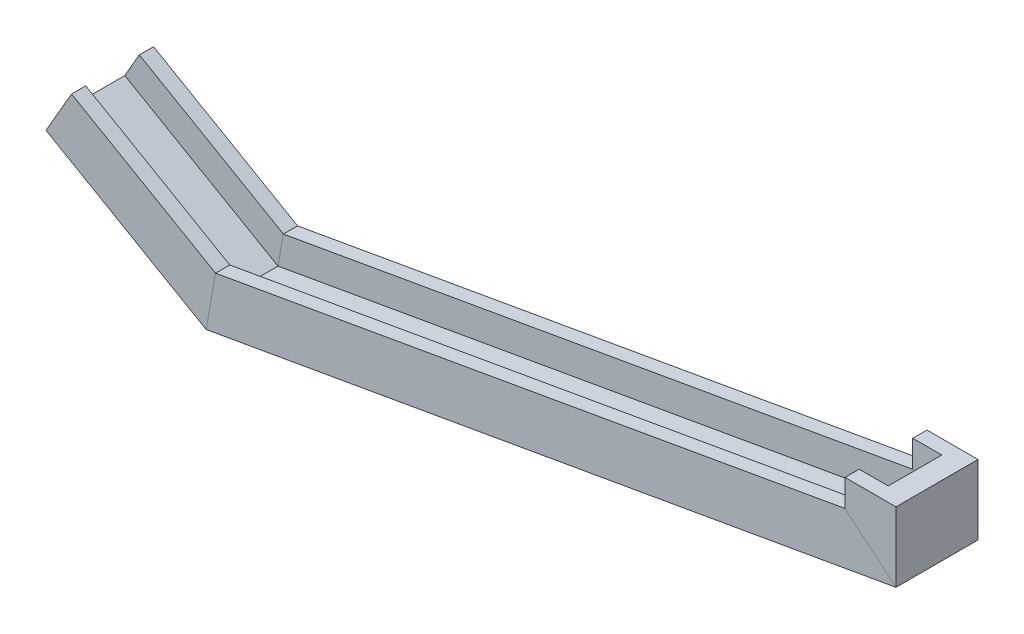
SolidWorks part; units mm, degrees
ref_plane "前视基准面" through (0, 0, 0) normal (0, 0, 1) x (1, 0, 0)
ref_plane "上视基准面" through (0, 0, 0) normal (0, 1, 0) x (1, 0, 0)
ref_plane "右视基准面" through (0, 0, 0) normal (1, 0, 0) x (0, 0, -1)
sketch "草图1" plane through (0, 0, 0) normal (0, 1, 0) x (1, 0, 0)
  line L0 (-24.3334, 21.5182) -> (-24.3334, 24.3032)
  line L1 (-24.3334, 21.5182) -> (-18.6403, 21.5182)
  line L2 (-18.6403, 21.5182) -> (-18.6403, 11.0182)
  line L3 (-18.6403, 11.0182) -> (-24.3334, 11.0182)
  line L4 (-24.3334, 11.0182) -> (-24.3334, 8.2332)
  line L5 (-24.3334, 8.2332) -> (-14.3334, 8.2332)
  line L6 (-14.3334, 8.2332) -> (-14.3334, 24.3032)
  line L7 (-24.3334, 24.3032) -> (-14.3334, 24.3032)
  line L8 (-19.3334, 8.2332) -> (-19.3334, 24.3032) construction
  line L9 (-19.3334, 16.2682) -> (-14.3334, 16.2682) construction
  point P5 (-19.3334, 16.2682)
  dimension "D1" = 10
  dimension "D2" = 16.07
  dimension "D3" = 10.5
  dimension "D4" = 2.785
ref_plane "基准面1" through (0, 0, -16.2682) normal (0, 0, -1) x (-1, 0, 0)
sketch "草图2" plane through (0, 0, -16.2682) normal (0, 0, -1) x (-1, 0, 0)
  line L0 (18.6934, 0) -> (18.6934, -10)
  line L1 (24.3334, 0) -> (14.3334, 0) construction
  line L2 (18.6934, -10) -> (148.6934, -32.9225)
  line L3 (148.6934, -32.9225) -> (178.6934, -15.602)
  dimension "D1" = 10
  dimension "D2" = 130
  dimension "D3" = 100
  dimension "D4" = 140
  dimension "D5" = 30
sweep "扫描2" add profiles "草图1" path "草图2"
